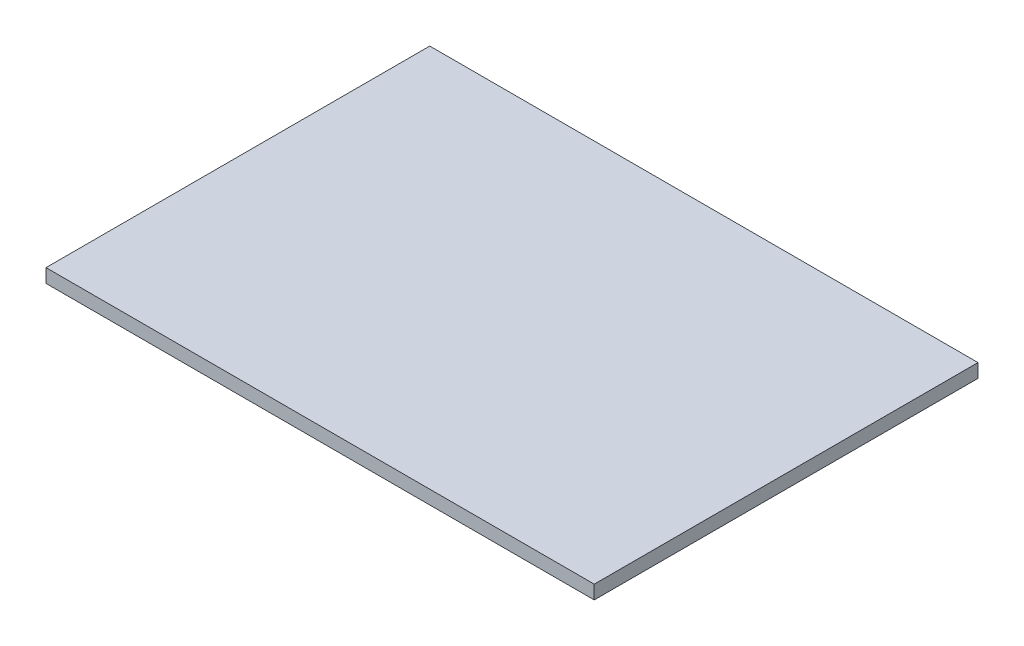
SolidWorks part; units mm, degrees
material "ABS"
ref_plane "Alzado" through (0, 0, 0) normal (0, 0, 1) x (1, 0, 0)
ref_plane "Planta" through (0, 0, 0) normal (0, 1, 0) x (1, 0, 0)
ref_plane "Vista lateral" through (0, 0, 0) normal (1, 0, 0) x (0, 0, -1)
sketch "Croquis1" plane through (0, 0, 0) normal (0, 1, 0) x (1, 0, 0)
  line L1 (0, 0) -> (200, 0)
  line L2 (0, 0) -> (0, 140)
  line L3 (0, 140) -> (200, 140)
  line L4 (200, 0) -> (200, 140)
  dimension "D1" = 140
  dimension "D2" = 200
extrude "Saliente-Extruir1" add sketch "Croquis1" along normal blind 5
